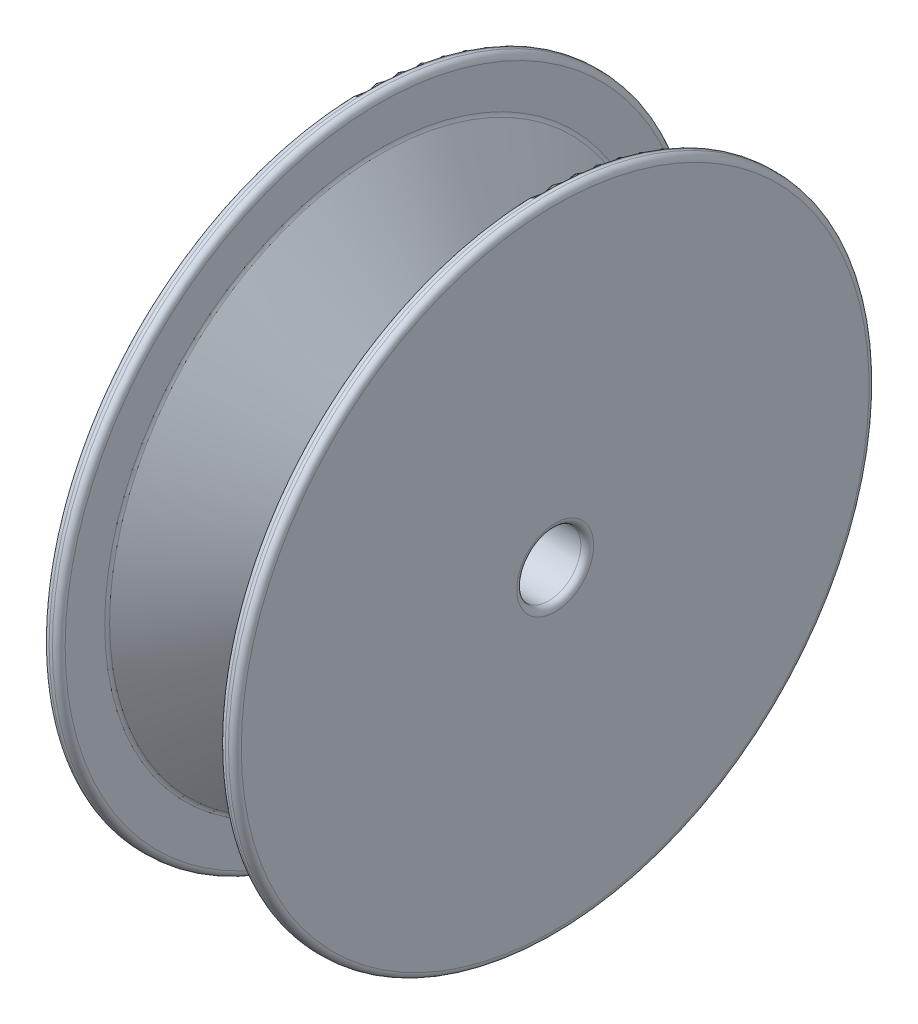
SolidWorks part; units mm, degrees
ref_plane "Face" through (0, 0, 0) normal (0, 0, 1) x (1, 0, 0)
ref_plane "Dessus" through (0, 0, 0) normal (0, 1, 0) x (1, 0, 0)
ref_plane "Droite" through (0, 0, 0) normal (1, 0, 0) x (0, 0, -1)
sketch "Esquisse1" plane through (0, 0, 0) normal (0, 0, 1) x (1, 0, 0)
  line L1 (-2.5, 8.5) -> (0, 5)
  line L3 (3, 1) -> (3, 10)
  line L4 (-3, 10) -> (-2.5, 10)
  line L5 (-3, 1) -> (-3, 10)
  line L6 (0, 5) -> (2.5, 8.5)
  line L7 (-2.5, 10) -> (-2.5, 8.5)
  line L8 (2.5, 8.5) -> (2.5, 10)
  line L9 (3, 10) -> (2.5, 10)
  line L10 (-3, 1) -> (3, 1)
  line L12 (0, 0) -> (68.6205, 0) construction
  dimension "D8" = 2.5
  dimension "D1" = 3
  dimension "D2" = 6
  dimension "D3" = 1.5
  dimension "D4" = 0.5
  dimension "D5" = 0.5
  dimension "D6" = 1
  dimension "D7" = 3.5
  dimension "D9" = 3.5
  dimension "D10" = 20
revolve "Révolution2" add sketch "Esquisse1" angle 360 about L12
fillet "Congé1" radius 0.2
sketch "Esquisse2" plane through (-3, 0, 0) normal (-1, 0, 0) x (0, 0, 1)
  line L0 (0, 0) -> (15.6118, 0) construction
  circle A0 centre (0, 6.53) radius 0.8434
  circle A1 centre (0, -6.53) radius 0.8434
extrude "Enlèv. mat.-Extru.1" cut sketch "Esquisse2" against normal blind 0.25
